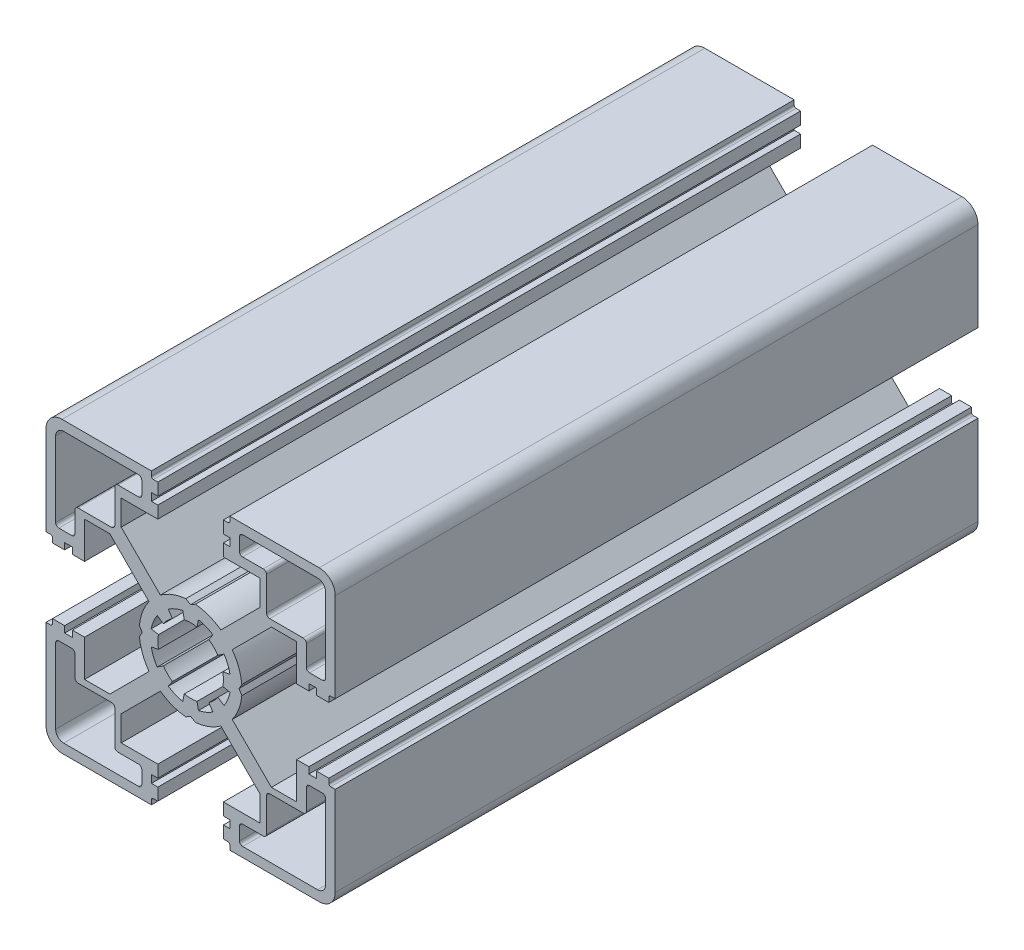
SolidWorks part; units mm, degrees
ref_plane "前视基准面" through (0, 0, 0) normal (0, 0, 1) x (1, 0, 0)
ref_plane "上视基准面" through (0, 0, 0) normal (0, 1, 0) x (1, 0, 0)
ref_plane "右视基准面" through (0, 0, 0) normal (1, 0, 0) x (0, 0, -1)
sketch "草图1" plane through (0, 0, 0) normal (0, 0, 1) x (1, 0, 0)
  line L0 (-5.3716, 21.743) -> (-19.2716, 21.743)
  line L1 (-21.7716, 19.243) -> (-21.7716, 5.343)
  line L2 (-4.3716, 15.743) -> (-10.0716, 15.743)
  line L3 (-15.7716, 10.043) -> (-15.7716, 4.343)
  line L4 (-19.7716, 6.843) -> (-17.7716, 6.843)
  line L5 (-17.2716, 7.343) -> (-17.2716, 10.543)
  line L6 (-16.7716, 11.043) -> (-11.5716, 11.043)
  line L7 (-11.0716, 11.543) -> (-11.0716, 16.743)
  line L8 (-10.5716, 17.243) -> (-7.3716, 17.243)
  line L9 (-6.8716, 17.743) -> (-6.8716, 19.743)
  line L10 (-7.3716, 20.243) -> (-19.0216, 20.243)
  line L11 (-20.2716, 18.993) -> (-20.2716, 7.343)
  line L12 (-4.3716, 20.743) -> (-5.0716, 20.743)
  line L13 (-5.3716, 21.043) -> (-5.3716, 21.743)
  line L14 (-21.7716, 5.343) -> (-21.0716, 5.343)
  line L15 (-20.7716, 5.043) -> (-20.7716, 4.343)
  line L16 (-15.7716, 10.043) -> (-11.8394, 10.043)
  line L17 (-18.8716, 5.343) -> (-17.6716, 5.343)
  line L18 (-20.7716, 4.343) -> (-18.8716, 4.343)
  line L19 (-17.6716, 4.343) -> (-15.7716, 4.343)
  line L20 (-10.0716, 15.743) -> (-10.0716, 11.8108)
  line L21 (-5.3716, 18.843) -> (-5.3716, 17.643)
  line L22 (-4.3716, 20.743) -> (-4.3716, 18.843)
  line L23 (-4.3716, 17.643) -> (-4.3716, 15.743)
  line L24 (-11.8394, 10.043) -> (-5.7428, 3.9465)
  line L25 (-10.0716, 11.8108) -> (-3.9751, 5.7142)
  line L26 (-4.3716, 17.643) -> (-5.3716, 17.643)
  line L27 (-4.3716, 18.843) -> (-5.3716, 18.843)
  line L28 (19.2284, -8.357) -> (21.2284, -8.357)
  line L29 (-17.6716, 4.343) -> (-17.6716, 5.343)
  line L30 (-18.8716, 4.343) -> (-18.8716, 5.343)
  line L31 (6.8284, 21.743) -> (20.7284, 21.743)
  line L32 (23.2284, 19.243) -> (23.2284, 5.343)
  line L33 (5.8284, 15.743) -> (11.5284, 15.743)
  line L34 (17.2284, 10.043) -> (17.2284, 4.343)
  line L35 (21.2284, 6.843) -> (19.2284, 6.843)
  line L36 (18.7284, 7.343) -> (18.7284, 10.543)
  line L37 (18.2284, 11.043) -> (13.0284, 11.043)
  line L38 (12.5284, 11.543) -> (12.5284, 16.743)
  line L39 (12.0284, 17.243) -> (8.8284, 17.243)
  line L40 (8.3284, 17.743) -> (8.3284, 19.743)
  line L41 (8.8284, 20.243) -> (20.4784, 20.243)
  line L42 (21.7284, 18.993) -> (21.7284, 7.343)
  line L43 (5.8284, 20.743) -> (6.5284, 20.743)
  line L44 (6.8284, 21.043) -> (6.8284, 21.743)
  line L45 (23.2284, 5.343) -> (22.5284, 5.343)
  line L46 (22.2284, 5.043) -> (22.2284, 4.343)
  line L47 (17.2284, 10.043) -> (13.2962, 10.043)
  line L48 (20.3284, 5.343) -> (19.1284, 5.343)
  line L49 (22.2284, 4.343) -> (20.3284, 4.343)
  line L50 (19.1284, 4.343) -> (17.2284, 4.343)
  line L51 (11.5284, 15.743) -> (11.5284, 11.8108)
  line L52 (6.8284, 18.843) -> (6.8284, 17.643)
  line L53 (13.2962, 10.043) -> (7.1997, 3.9465)
  line L54 (11.5284, 11.8108) -> (5.4319, 5.7142)
  line L55 (5.8284, 17.643) -> (6.8284, 17.643)
  line L56 (5.8284, 18.843) -> (6.8284, 18.843)
  line L58 (19.1284, 4.343) -> (19.1284, 5.343)
  line L59 (20.3284, 4.343) -> (20.3284, 5.343)
  line L60 (5.8284, 20.743) -> (5.8284, 18.843)
  line L61 (5.8284, 17.643) -> (5.8284, 15.743)
  line L62 (-5.3716, -23.257) -> (-19.2716, -23.257)
  line L63 (-21.7716, -20.757) -> (-21.7716, -6.857)
  line L64 (-4.3716, -17.257) -> (-10.0716, -17.257)
  line L65 (-15.7716, -11.557) -> (-15.7716, -5.857)
  line L66 (-19.7716, -8.357) -> (-17.7716, -8.357)
  line L67 (-17.2716, -8.857) -> (-17.2716, -12.057)
  line L68 (-16.7716, -12.557) -> (-11.5716, -12.557)
  line L69 (-11.0716, -13.057) -> (-11.0716, -18.257)
  line L70 (-10.5716, -18.757) -> (-7.3716, -18.757)
  line L71 (-6.8716, -19.257) -> (-6.8716, -21.257)
  line L72 (-7.3716, -21.757) -> (-19.0216, -21.757)
  line L73 (-20.2716, -20.507) -> (-20.2716, -8.857)
  line L74 (-4.3716, -22.257) -> (-5.0716, -22.257)
  line L75 (-5.3716, -22.557) -> (-5.3716, -23.257)
  line L76 (-21.7716, -6.857) -> (-21.0716, -6.857)
  line L77 (-20.7716, -6.557) -> (-20.7716, -5.857)
  line L78 (-15.7716, -11.557) -> (-11.8394, -11.557)
  line L79 (-18.8716, -6.857) -> (-17.6716, -6.857)
  line L80 (-20.7716, -5.857) -> (-18.8716, -5.857)
  line L81 (-17.6716, -5.857) -> (-15.7716, -5.857)
  line L82 (-10.0716, -17.257) -> (-10.0716, -13.3248)
  line L83 (-5.3716, -20.357) -> (-5.3716, -19.157)
  line L84 (-4.3716, -22.257) -> (-4.3716, -20.357)
  line L85 (-4.3716, -19.157) -> (-4.3716, -17.257)
  line L86 (-11.8394, -11.557) -> (-5.7428, -5.4605)
  line L87 (-10.0716, -13.3248) -> (-3.9751, -7.2283)
  line L88 (-4.3716, -19.157) -> (-5.3716, -19.157)
  line L89 (-4.3716, -20.357) -> (-5.3716, -20.357)
  line L91 (-17.6716, -5.857) -> (-17.6716, -6.857)
  line L92 (-18.8716, -5.857) -> (-18.8716, -6.857)
  line L93 (6.8284, -23.257) -> (20.7284, -23.257)
  line L94 (23.2284, -20.757) -> (23.2284, -6.857)
  line L95 (5.8284, -17.257) -> (11.5284, -17.257)
  line L96 (17.2284, -11.557) -> (17.2284, -5.857)
  line L97 (18.7284, -8.857) -> (18.7284, -12.057)
  line L98 (18.2284, -12.557) -> (13.0284, -12.557)
  line L99 (12.5284, -13.057) -> (12.5284, -18.257)
  line L100 (12.0284, -18.757) -> (8.8284, -18.757)
  line L101 (8.3284, -19.257) -> (8.3284, -21.257)
  line L102 (8.8284, -21.757) -> (20.4784, -21.757)
  line L103 (21.7284, -20.507) -> (21.7284, -8.857)
  line L104 (5.8284, -22.257) -> (6.5284, -22.257)
  line L105 (6.8284, -22.557) -> (6.8284, -23.257)
  line L106 (23.2284, -6.857) -> (22.5284, -6.857)
  line L107 (22.2284, -6.557) -> (22.2284, -5.857)
  line L108 (17.2284, -11.557) -> (13.2962, -11.557)
  line L109 (20.3284, -6.857) -> (19.1284, -6.857)
  line L110 (22.2284, -5.857) -> (20.3284, -5.857)
  line L111 (19.1284, -5.857) -> (17.2284, -5.857)
  line L112 (11.5284, -17.257) -> (11.5284, -13.3248)
  line L113 (6.8284, -20.357) -> (6.8284, -19.157)
  line L114 (13.2962, -11.557) -> (7.1997, -5.4605)
  line L115 (11.5284, -13.3248) -> (5.4319, -7.2283)
  line L116 (5.8284, -19.157) -> (6.8284, -19.157)
  line L117 (5.8284, -20.357) -> (6.8284, -20.357)
  line L119 (19.1284, -5.857) -> (19.1284, -6.857)
  line L120 (20.3284, -5.857) -> (20.3284, -6.857)
  line L121 (5.8284, -22.257) -> (5.8284, -20.357)
  line L122 (5.8284, -19.157) -> (5.8284, -17.257)
  line L123 (-2.7439, -5.9537) -> (-2.105, -4.9975)
  line L124 (-0.4909, -6.8869) -> (-0.2665, -5.759)
  line L125 (1.9477, -6.8869) -> (1.7234, -5.759)
  line L126 (4.2007, -5.9537) -> (3.5618, -4.9975)
  line L127 (5.9251, -4.2293) -> (4.9689, -3.5904)
  line L128 (6.8583, -1.9763) -> (5.7304, -1.752)
  line L129 (6.8583, 0.4623) -> (5.7304, 0.2379)
  line L130 (5.9251, 2.7153) -> (4.9689, 2.0764)
  line L131 (4.2007, 4.4397) -> (3.5618, 3.4835)
  line L132 (1.9477, 5.3729) -> (1.7234, 4.245)
  line L133 (-0.4909, 5.3729) -> (-0.2665, 4.245)
  line L134 (-2.7439, 4.4397) -> (-2.105, 3.4835)
  line L135 (-4.4683, 2.7153) -> (-3.5121, 2.0764)
  line L136 (-5.4015, 0.4623) -> (-4.2736, 0.2379)
  line L137 (-5.4015, -1.9763) -> (-4.2736, -1.752)
  line L138 (-4.4683, -4.2293) -> (-3.5121, -3.5904)
  line L139 (0.7284, 6.7747) -> (1.4784, 7.2078)
  line L140 (0.7284, 6.7747) -> (-0.0216, 7.2078)
  line L141 (0.7284, -8.2888) -> (1.4784, -8.7218)
  line L142 (0.7284, -8.2888) -> (-0.0216, -8.7218)
  line L143 (-6.8033, -0.757) -> (-7.2364, -1.507)
  line L144 (-6.8033, -0.757) -> (-7.2364, -0.007)
  line L145 (8.2602, -0.757) -> (8.6932, -1.507)
  line L146 (8.2602, -0.757) -> (8.6932, -0.007)
  arc A0 (-19.2716, 21.743) -> (-21.7716, 19.243) centre (-19.2716, 19.243) ccw
  arc A1 (-17.7716, 6.843) -> (-17.2716, 7.343) centre (-17.7716, 7.343) ccw
  arc A2 (-16.7716, 11.043) -> (-17.2716, 10.543) centre (-16.7716, 10.543) ccw
  arc A3 (-11.5716, 11.043) -> (-11.0716, 11.543) centre (-11.5716, 11.543) ccw
  arc A4 (-10.5716, 17.243) -> (-11.0716, 16.743) centre (-10.5716, 16.743) ccw
  arc A5 (-7.3716, 17.243) -> (-6.8716, 17.743) centre (-7.3716, 17.743) ccw
  arc A6 (-6.8716, 19.743) -> (-7.3716, 20.243) centre (-7.3716, 19.743) ccw
  arc A7 (-19.0216, 20.243) -> (-20.2716, 18.993) centre (-19.0216, 18.993) ccw
  arc A8 (-20.2716, 7.343) -> (-19.7716, 6.843) centre (-19.7716, 7.343) ccw
  arc A9 (-5.3716, 21.043) -> (-5.0716, 20.743) centre (-5.0716, 21.043) ccw
  arc A10 (-20.7716, 5.043) -> (-21.0716, 5.343) centre (-21.0716, 5.043) ccw
  arc A11 (-3.5121, -3.5904) -> (-2.105, -4.9975) centre (0.7284, -0.757) ccw
  arc A12 (-0.2665, -5.759) -> (1.7234, -5.759) centre (0.7284, -0.757) ccw
  arc A13 (3.5618, -4.9975) -> (4.9689, -3.5904) centre (0.7284, -0.757) ccw
  arc A14 (5.7304, -1.752) -> (5.7304, 0.2379) centre (0.7284, -0.757) ccw
  arc A15 (4.9689, 2.0764) -> (3.5618, 3.4835) centre (0.7284, -0.757) ccw
  arc A16 (1.7234, 4.245) -> (-0.2665, 4.245) centre (0.7284, -0.757) ccw
  arc A17 (-2.105, 3.4835) -> (-3.5121, 2.0764) centre (0.7284, -0.757) ccw
  arc A18 (-4.2736, 0.2379) -> (-4.2736, -1.752) centre (0.7284, -0.757) ccw
  arc A19 (-2.7439, -5.9537) -> (-0.4909, -6.8869) centre (0.7284, -0.757) ccw
  arc A20 (1.9477, -6.8869) -> (4.2007, -5.9537) centre (0.7284, -0.757) ccw
  arc A21 (5.9251, -4.2293) -> (6.8583, -1.9763) centre (0.7284, -0.757) ccw
  arc A22 (6.8583, 0.4623) -> (5.9251, 2.7153) centre (0.7284, -0.757) ccw
  arc A23 (4.2007, 4.4397) -> (1.9477, 5.3729) centre (0.7284, -0.757) ccw
  arc A24 (-0.4909, 5.3729) -> (-2.7439, 4.4397) centre (0.7284, -0.757) ccw
  arc A25 (-4.4683, 2.7153) -> (-5.4015, 0.4623) centre (0.7284, -0.757) ccw
  arc A26 (-5.4015, -1.9763) -> (-4.4683, -4.2293) centre (0.7284, -0.757) ccw
  arc A27 (-5.7428, 3.9465) -> (-7.2364, -0.007) centre (0.7284, -0.757) ccw
  arc A28 (-7.2364, -1.507) -> (-5.7428, -5.4605) centre (0.7284, -0.757) ccw
  arc A29 (-3.9751, -7.2283) -> (-0.0216, -8.7218) centre (0.7284, -0.757) ccw
  arc A30 (1.4784, -8.7218) -> (5.4319, -7.2283) centre (0.7284, -0.757) ccw
  arc A31 (7.1997, -5.4605) -> (8.6932, -1.507) centre (0.7284, -0.757) ccw
  arc A32 (8.6932, -0.007) -> (7.1997, 3.9465) centre (0.7284, -0.757) ccw
  arc A33 (5.4319, 5.7142) -> (1.4784, 7.2078) centre (0.7284, -0.757) ccw
  arc A34 (-0.0216, 7.2078) -> (-3.9751, 5.7142) centre (0.7284, -0.757) ccw
  arc A35 (23.2284, 19.243) -> (20.7284, 21.743) centre (20.7284, 19.243) ccw
  arc A36 (18.7284, 7.343) -> (19.2284, 6.843) centre (19.2284, 7.343) ccw
  arc A37 (18.7284, 10.543) -> (18.2284, 11.043) centre (18.2284, 10.543) ccw
  arc A38 (12.5284, 11.543) -> (13.0284, 11.043) centre (13.0284, 11.543) ccw
  arc A39 (12.5284, 16.743) -> (12.0284, 17.243) centre (12.0284, 16.743) ccw
  arc A40 (8.3284, 17.743) -> (8.8284, 17.243) centre (8.8284, 17.743) ccw
  arc A41 (8.8284, 20.243) -> (8.3284, 19.743) centre (8.8284, 19.743) ccw
  arc A42 (21.7284, 18.993) -> (20.4784, 20.243) centre (20.4784, 18.993) ccw
  arc A43 (21.2284, 6.843) -> (21.7284, 7.343) centre (21.2284, 7.343) ccw
  arc A44 (6.5284, 20.743) -> (6.8284, 21.043) centre (6.5284, 21.043) ccw
  arc A45 (22.5284, 5.343) -> (22.2284, 5.043) centre (22.5284, 5.043) ccw
  arc A46 (-21.7716, -20.757) -> (-19.2716, -23.257) centre (-19.2716, -20.757) ccw
  arc A47 (-17.2716, -8.857) -> (-17.7716, -8.357) centre (-17.7716, -8.857) ccw
  arc A48 (-17.2716, -12.057) -> (-16.7716, -12.557) centre (-16.7716, -12.057) ccw
  arc A49 (-11.0716, -13.057) -> (-11.5716, -12.557) centre (-11.5716, -13.057) ccw
  arc A50 (-11.0716, -18.257) -> (-10.5716, -18.757) centre (-10.5716, -18.257) ccw
  arc A51 (-6.8716, -19.257) -> (-7.3716, -18.757) centre (-7.3716, -19.257) ccw
  arc A52 (-7.3716, -21.757) -> (-6.8716, -21.257) centre (-7.3716, -21.257) ccw
  arc A53 (-20.2716, -20.507) -> (-19.0216, -21.757) centre (-19.0216, -20.507) ccw
  arc A54 (-19.7716, -8.357) -> (-20.2716, -8.857) centre (-19.7716, -8.857) ccw
  arc A55 (-5.0716, -22.257) -> (-5.3716, -22.557) centre (-5.0716, -22.557) ccw
  arc A56 (-21.0716, -6.857) -> (-20.7716, -6.557) centre (-21.0716, -6.557) ccw
  arc A57 (20.7284, -23.257) -> (23.2284, -20.757) centre (20.7284, -20.757) ccw
  arc A58 (19.2284, -8.357) -> (18.7284, -8.857) centre (19.2284, -8.857) ccw
  arc A59 (18.2284, -12.557) -> (18.7284, -12.057) centre (18.2284, -12.057) ccw
  arc A60 (13.0284, -12.557) -> (12.5284, -13.057) centre (13.0284, -13.057) ccw
  arc A61 (12.0284, -18.757) -> (12.5284, -18.257) centre (12.0284, -18.257) ccw
  arc A62 (8.8284, -18.757) -> (8.3284, -19.257) centre (8.8284, -19.257) ccw
  arc A63 (8.3284, -21.257) -> (8.8284, -21.757) centre (8.8284, -21.257) ccw
  arc A64 (20.4784, -21.757) -> (21.7284, -20.507) centre (20.4784, -20.507) ccw
  arc A65 (21.7284, -8.857) -> (21.2284, -8.357) centre (21.2284, -8.857) ccw
  arc A66 (6.8284, -22.557) -> (6.5284, -22.257) centre (6.5284, -22.557) ccw
  arc A67 (22.2284, -6.557) -> (22.5284, -6.857) centre (22.5284, -6.557) ccw
extrude "凸台-拉伸1" add sketch "草图1" along normal blind 100
